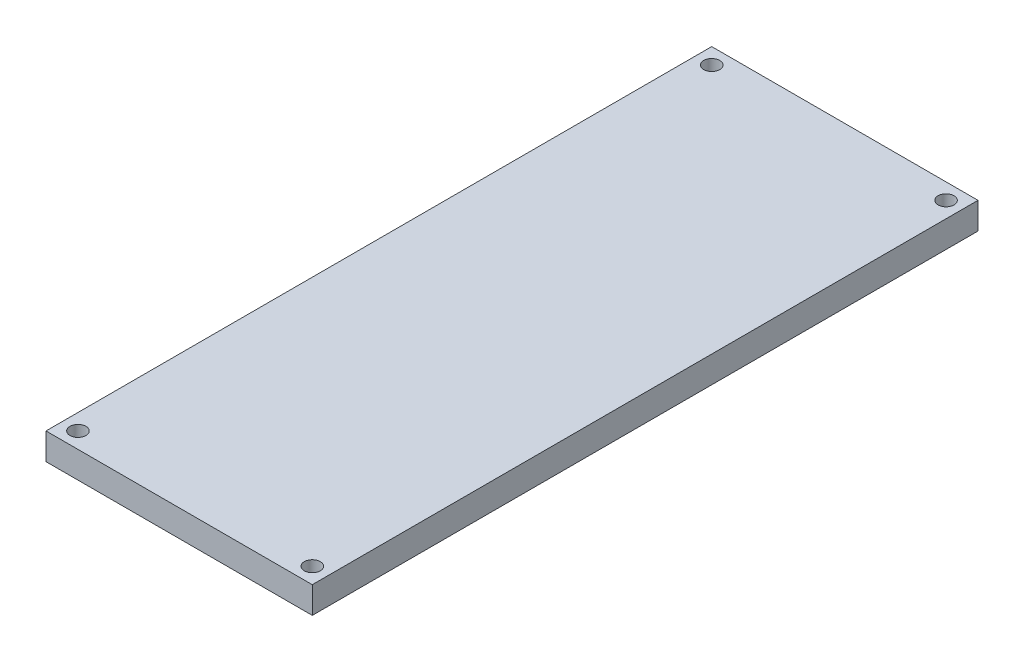
SolidWorks part; units mm, degrees
ref_plane "Front Plane" through (0, 0, 0) normal (0, 0, 1) x (1, 0, 0)
ref_plane "Top Plane" through (0, 0, 0) normal (0, 1, 0) x (1, 0, 0)
ref_plane "Right Plane" through (0, 0, 0) normal (1, 0, 0) x (0, 0, -1)
sketch "Sketch1" plane through (0, 0, 0) normal (0, 1, 0) x (1, 0, 0)
  line L1 (0, 0) -> (50, 0)
  line L2 (0, 0) -> (0, 125)
  line L3 (0, 125) -> (50, 125)
  line L4 (50, 0) -> (50, 125)
  dimension "D1" = 125
  dimension "D2" = 50
extrude "Boss-Extrude1" add sketch "Sketch1" along normal blind 5
sketch "Sketch2" plane through (0, 5, 0) normal (0, 1, 0) x (1, 0, 0)
  line L4 (3, 3) -> (3, 0) construction
  line L5 (0, 0) -> (50, 0) construction
  line L6 (47, 3) -> (47, 0) construction
  line L7 (3, 122) -> (3, 125) construction
  line L8 (50, 125) -> (0, 125) construction
  line L9 (3, 122) -> (0, 122) construction
  line L10 (0, 125) -> (0, 0) construction
  line L11 (47, 125) -> (47, 122) construction
  line L12 (47, 122) -> (50, 122) construction
  line L13 (50, 0) -> (50, 125) construction
  line L14 (3, 3) -> (0, 3) construction
  line L15 (47, 3) -> (50, 3) construction
  circle A0 centre (3, 122) radius 1.5
  circle A1 centre (47, 122) radius 1.5
  circle A2 centre (3, 3) radius 1.5
  circle A3 centre (47, 3) radius 1.5
  dimension "D5" = 3
  dimension "D6" = 3
  dimension "D7" = 3
  dimension "D8" = 3
  dimension "D9" = 3
  dimension "D1" = 3
  dimension "D2" = 3
  dimension "D3" = 3
  dimension "D4" = 3
  dimension "D10" = 3
  dimension "D11" = 3
  dimension "D12" = 3
extrude "Cut-Extrude2" cut sketch "Sketch2" against normal through all
